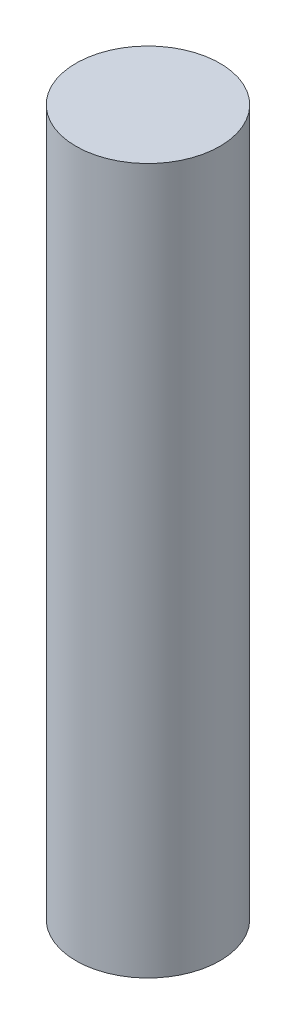
SolidWorks part; units mm, degrees
material "Alloy Steel"
ref_plane "Front Plane" through (0, 0, 0) normal (0, 0, 1) x (1, 0, 0)
ref_plane "Top Plane" through (0, 0, 0) normal (0, 1, 0) x (1, 0, 0)
ref_plane "Right Plane" through (0, 0, 0) normal (1, 0, 0) x (0, 0, -1)
sketch "Sketch1" plane through (0, 0, 0) normal (0, 1, 0) x (1, 0, 0)
  circle A0 centre (0, 0) radius 2.5
  dimension "D1" = 5
extrude "Boss-Extrude1" add sketch "Sketch1" along normal blind 24.5
